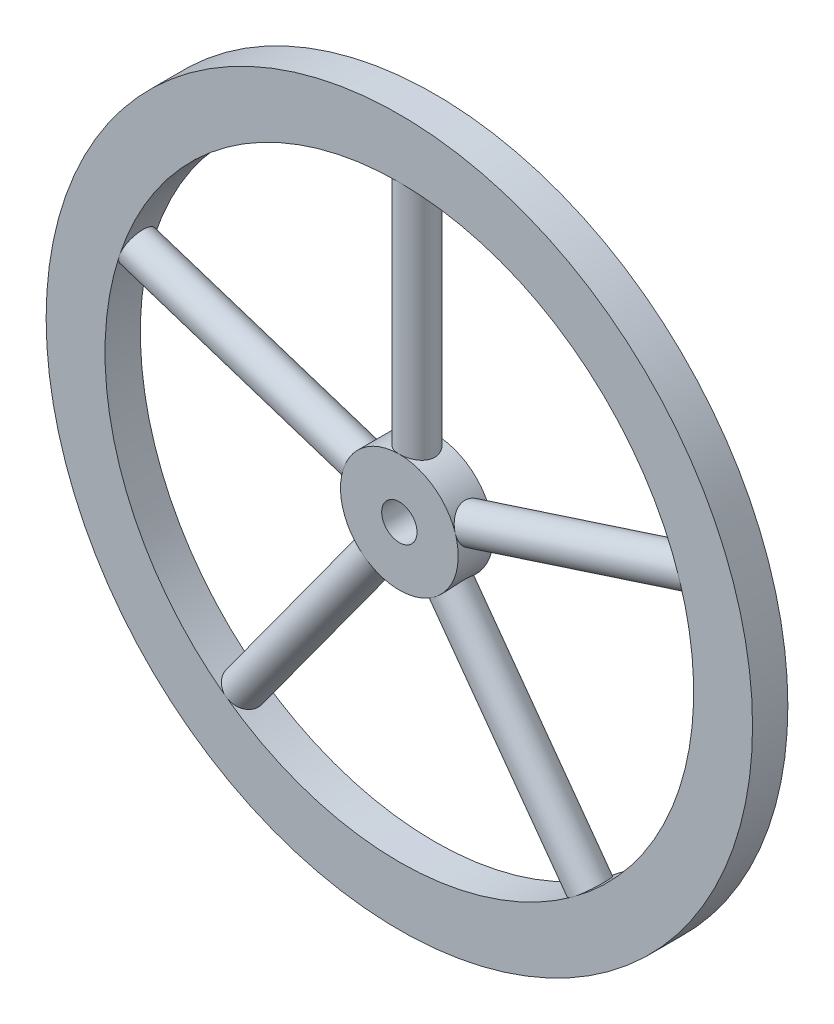
SolidWorks part; units mm, degrees
ref_plane "Front Plane" through (0, 0, 0) normal (0, 0, 1) x (1, 0, 0)
ref_plane "Top Plane" through (0, 0, 0) normal (0, 1, 0) x (1, 0, 0)
ref_plane "Right Plane" through (0, 0, 0) normal (1, 0, 0) x (0, 0, -1)
sketch "Sketch1" plane through (0, 0, 0) normal (0, 0, 1) x (1, 0, 0)
  circle A0 centre (0, 0) radius 250
  circle A1 centre (0, 0) radius 50
  circle A2 centre (0, 0) radius 15
  circle A3 centre (0, 0) radius 300
  dimension "D1" = 30
  dimension "D2" = 100
  dimension "D3" = 500
  dimension "D4" = 600
extrude "Boss-Extrude1" add sketch "Sketch1" along normal mid plane 30 contours A3 A0 | A1 A2
sketch "Sketch3" plane through (0, 0, 0) normal (0, 0, 1) x (1, 0, 0)
  line L0 (0, 0) -> (0, 330.2044) construction
  line L2 (0, 263.2383) -> (15, 263.2383)
  line L3 (0, 263.2383) -> (0, 36.9098)
  line L4 (0, 36.9098) -> (15, 36.9098)
  line L5 (15, 263.2383) -> (15, 36.9098)
  point P8 (15, 263.2383)
  point P9 (0, 0)
  point P10 (18.6488, 272.5627)
  point P11 (15, 36.9098)
  dimension "D1" = 15
revolve "Revolve1" add sketch "Sketch3" angle 360 about L0
pattern_circular "CirPattern1" count 5 over 360 about axis through (0, 0, 15) along (0, 0, -1) of "Revolve1"
